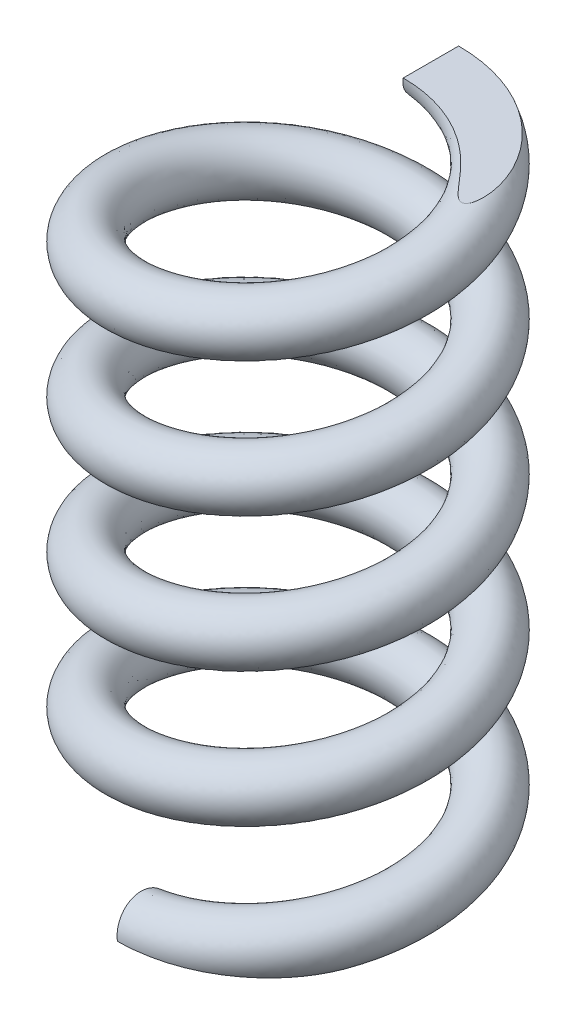
SolidWorks part; units mm, degrees
ref_plane "Front Plane" through (0, 0, 0) normal (0, 0, 1) x (1, 0, 0)
ref_plane "Top Plane" through (0, 0, 0) normal (0, 1, 0) x (1, 0, 0)
ref_plane "Right Plane" through (0, 0, 0) normal (1, 0, 0) x (0, 0, -1)
sketch "Sketch2" plane through (0, 0, 0) normal (0, 1, 0) x (1, 0, 0)
  circle A0 centre (0, 0) radius 19.85
  dimension "D1" = 39.7
curve "Helix/Spiral1" pitch 18.6667 height 84 turns 4.5
ref_plane "Plane1" through (0, 0, 19.85) normal (0.989, 0.148, 0) x (0, 0, -1)
sketch "Sketch4" plane through (0, 0, 19.85) normal (0.989, 0.148, 0) x (0, 0, -1)
  circle A0 centre (0, 0) radius 3.85
  dimension "D2" = 7.7
  dimension "D1" = 19.85
sweep "Sweep1" add profiles "Sketch4" path "Helix/Spiral1"
sketch "Sketch5" plane through (0, 0, 0) normal (0, 1, 0) x (1, 0, 0)
  circle A0 centre (0, 0) radius 41.5067
extrude "Cut-Extrude1" cut sketch "Sketch5" against normal blind 10
ref_plane "Plane2" through (0, 84, 0) normal (0, 1, 0) x (-1, 0, 0)
sketch "Sketch6" plane through (0, 84, 0) normal (0, 1, 0) x (-1, 0, 0)
  circle A0 centre (0, 0) radius 43.0394
extrude "Cut-Extrude2" cut sketch "Sketch6" along normal blind 10
